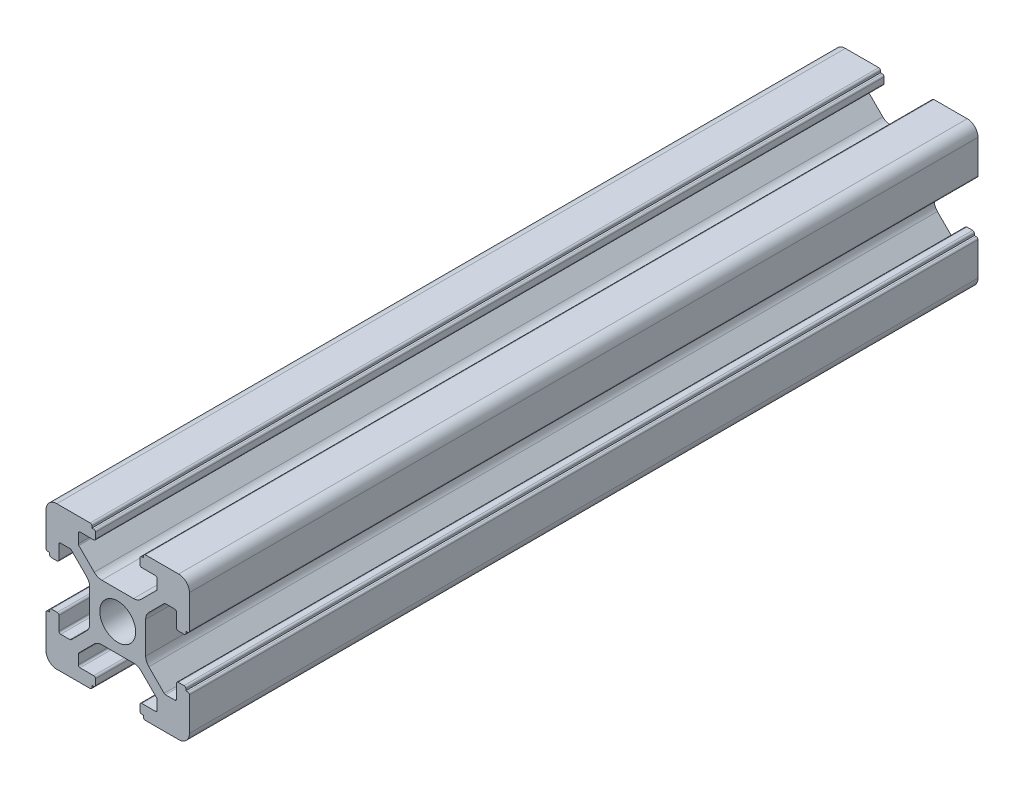
SolidWorks part; units mm, degrees
ref_plane "前视基准面" through (0, 0, 0) normal (0, 0, 1) x (1, 0, 0)
ref_plane "上视基准面" through (0, 0, 0) normal (0, 1, 0) x (1, 0, 0)
ref_plane "右视基准面" through (0, 0, 0) normal (1, 0, 0) x (0, 0, -1)
sketch "草图1" plane through (0, 0, 0) normal (0, 0, 1) x (1, 0, 0)
  line L0 (0, 0) -> (0, 5.5) construction
  line L1 (-8.5023, -10.0023) -> (-3.85, -10.0023)
  line L2 (-10.0023, -8.5023) -> (-10.0023, -3.85)
  line L3 (-8.5023, 10.0023) -> (-3.85, 10.0023)
  line L4 (10.0023, -8.5023) -> (10.0023, -3.85)
  line L5 (-10.0023, -10.0023) -> (10.0023, 10.0023) construction
  line L6 (-10.0023, 10.0023) -> (10.0023, -10.0023) construction
  line L7 (-2.218, -3.9) -> (2.218, -3.9)
  line L8 (-3.9, -2.218) -> (-3.9, 2.218)
  line L9 (-2.218, 3.9) -> (2.218, 3.9)
  line L10 (3.9, -2.218) -> (3.9, 2.218)
  line L11 (-3.9, -3.9) -> (3.9, 3.9) construction
  line L12 (-3.9, 3.9) -> (3.9, -3.9) construction
  line L13 (-5.25, -8.2) -> (-3.35, -8.2)
  line L14 (-8.2, -5.25) -> (-8.2, -3.35)
  line L15 (-5.25, 8.2) -> (-3.35, 8.2)
  line L16 (8.2, -5.25) -> (8.2, -3.35)
  line L17 (-8.2, -8.2) -> (8.2, 8.2) construction
  line L18 (-8.2, 8.2) -> (8.2, -8.2) construction
  line L19 (-7.95, 5.5) -> (-6.6642, 5.5)
  line L20 (0, 0) -> (5.5, 0) construction
  line L23 (-5.5, 7.95) -> (-5.5, 6.6642)
  line L26 (0, 0) -> (-0.5303, 0.5303)
  line L27 (3.2787, 4.3393) -> (5.4268, 6.4874)
  line L28 (0, 0) -> (0.5303, -0.5303)
  line L29 (5.5, 6.6642) -> (5.5, 7.95)
  line L30 (4.3393, 3.2787) -> (6.4874, 5.4268)
  line L31 (6.6642, 5.5) -> (7.95, 5.5)
  line L32 (4.3393, -3.2787) -> (6.4874, -5.4268)
  line L33 (3.2787, -4.3393) -> (5.4268, -6.4874)
  line L34 (-3.2787, -4.3393) -> (-5.4268, -6.4874)
  line L35 (-4.3393, -3.2787) -> (-6.4874, -5.4268)
  line L36 (-4.3393, 3.2787) -> (-6.4874, 5.4268)
  line L37 (-3.2787, 4.3393) -> (-5.4268, 6.4874)
  line L38 (3.1, -8.45) -> (3.1, -9.2523)
  line L39 (8.45, 3.1) -> (9.2523, 3.1)
  line L40 (-5.5, -6.6642) -> (-5.5, -7.95)
  line L41 (-6.6642, -5.5) -> (-7.95, -5.5)
  line L42 (5.5, -6.6642) -> (5.5, -7.95)
  line L43 (6.6642, -5.5) -> (7.95, -5.5)
  line L44 (9.2523, -3.1) -> (8.45, -3.1)
  line L46 (10.0023, 3.85) -> (10.0023, 8.5023)
  line L47 (8.2, 3.35) -> (8.2, 5.25)
  line L48 (-3.1, -9.2523) -> (-3.1, -8.45)
  line L49 (-8.45, -3.1) -> (-9.2523, -3.1)
  line L50 (-9.2523, 3.1) -> (-8.45, 3.1)
  line L51 (-3.1, 8.45) -> (-3.1, 9.2523)
  line L52 (3.1, 9.2523) -> (3.1, 8.45)
  line L53 (3.85, 10.0023) -> (8.5023, 10.0023)
  line L54 (3.35, 8.2) -> (5.25, 8.2)
  line L55 (-10.0023, 3.85) -> (-10.0023, 8.5023)
  line L56 (-8.2, 3.35) -> (-8.2, 5.25)
  line L57 (3.35, -8.2) -> (5.25, -8.2)
  line L58 (3.85, -10.0023) -> (8.5023, -10.0023)
  line L59 (9.7523, -3.6) -> (9.5023, -3.6)
  line L61 (9.7523, 3.6) -> (9.5023, 3.6)
  line L62 (9.5023, -3.6) -> (9.5023, -3.35)
  line L63 (3.6, -9.7523) -> (3.6, -9.5023)
  line L64 (3.35, -9.5023) -> (3.6, -9.5023)
  line L65 (9.5023, 3.35) -> (9.5023, 3.6)
  line L66 (-3.6, -9.5023) -> (-3.35, -9.5023)
  line L67 (-3.6, -9.7523) -> (-3.6, -9.5023)
  line L68 (-9.7523, -3.6) -> (-9.5023, -3.6)
  line L69 (-9.5023, -3.35) -> (-9.5023, -3.6)
  line L70 (-9.5023, 3.6) -> (-9.5023, 3.35)
  line L71 (-9.7523, 3.6) -> (-9.5023, 3.6)
  line L72 (-3.6, 9.7523) -> (-3.6, 9.5023)
  line L73 (-3.35, 9.5023) -> (-3.6, 9.5023)
  line L74 (3.6, 9.5023) -> (3.35, 9.5023)
  line L75 (3.6, 9.7523) -> (3.6, 9.5023)
  circle A0 centre (0, 0) radius 2.5
  arc A1 (10.0023, 8.5023) -> (8.5023, 10.0023) centre (8.5023, 8.5023) ccw
  arc A2 (8.5023, -10.0023) -> (10.0023, -8.5023) centre (8.5023, -8.5023) ccw
  arc A3 (-10.0023, -8.5023) -> (-8.5023, -10.0023) centre (-8.5023, -8.5023) ccw
  arc A4 (-10.0023, 8.5023) -> (-8.5023, 10.0023) centre (-8.5023, 8.5023) cw
  arc A5 (-9.5023, -3.35) -> (-9.2523, -3.1) centre (-9.2523, -3.35) cw
  arc A6 (-9.7523, -3.6) -> (-10.0023, -3.85) centre (-9.7523, -3.85) ccw
  arc A7 (-8.45, -3.1) -> (-8.2, -3.35) centre (-8.45, -3.35) cw
  arc A8 (-7.95, -5.5) -> (-8.2, -5.25) centre (-7.95, -5.25) cw
  arc A9 (-6.4874, -5.4268) -> (-6.6642, -5.5) centre (-6.6642, -5.25) cw
  arc A10 (-5.4268, -6.4874) -> (-5.5, -6.6642) centre (-5.25, -6.6642) ccw
  arc A11 (-5.5, -7.95) -> (-5.25, -8.2) centre (-5.25, -7.95) ccw
  arc A12 (-3.6, -9.7523) -> (-3.85, -10.0023) centre (-3.85, -9.7523) cw
  arc A13 (-3.35, -9.5023) -> (-3.1, -9.2523) centre (-3.35, -9.2523) ccw
  arc A14 (-3.1, -8.45) -> (-3.35, -8.2) centre (-3.35, -8.45) ccw
  arc A15 (3.1, -8.45) -> (3.35, -8.2) centre (3.35, -8.45) cw
  arc A16 (5.5, -7.95) -> (5.25, -8.2) centre (5.25, -7.95) cw
  arc A17 (5.4268, -6.4874) -> (5.5, -6.6642) centre (5.25, -6.6642) cw
  arc A18 (6.4874, -5.4268) -> (6.6642, -5.5) centre (6.6642, -5.25) ccw
  arc A19 (7.95, -5.5) -> (8.2, -5.25) centre (7.95, -5.25) ccw
  arc A20 (8.45, -3.1) -> (8.2, -3.35) centre (8.45, -3.35) ccw
  arc A21 (9.5023, -3.35) -> (9.2523, -3.1) centre (9.2523, -3.35) ccw
  arc A22 (9.7523, -3.6) -> (10.0023, -3.85) centre (9.7523, -3.85) cw
  arc A23 (3.35, -9.5023) -> (3.1, -9.2523) centre (3.35, -9.2523) cw
  arc A24 (3.6, -9.7523) -> (3.85, -10.0023) centre (3.85, -9.7523) ccw
  arc A25 (7.95, 5.5) -> (8.2, 5.25) centre (7.95, 5.25) cw
  arc A26 (8.2, 3.35) -> (8.45, 3.1) centre (8.45, 3.35) ccw
  arc A27 (9.5023, 3.35) -> (9.2523, 3.1) centre (9.2523, 3.35) cw
  arc A28 (9.7523, 3.6) -> (10.0023, 3.85) centre (9.7523, 3.85) ccw
  arc A29 (6.6642, 5.5) -> (6.4874, 5.4268) centre (6.6642, 5.25) ccw
  arc A30 (5.4268, 6.4874) -> (5.5, 6.6642) centre (5.25, 6.6642) ccw
  arc A31 (5.5, 7.95) -> (5.25, 8.2) centre (5.25, 7.95) ccw
  arc A32 (3.1, 8.45) -> (3.35, 8.2) centre (3.35, 8.45) ccw
  arc A33 (3.6, 9.7523) -> (3.85, 10.0023) centre (3.85, 9.7523) cw
  arc A34 (3.35, 9.5023) -> (3.1, 9.2523) centre (3.35, 9.2523) ccw
  arc A35 (-9.7523, 3.6) -> (-10.0023, 3.85) centre (-9.7523, 3.85) cw
  arc A36 (-9.5023, 3.35) -> (-9.2523, 3.1) centre (-9.2523, 3.35) ccw
  arc A37 (-8.45, 3.1) -> (-8.2, 3.35) centre (-8.45, 3.35) ccw
  arc A38 (-8.2, 5.25) -> (-7.95, 5.5) centre (-7.95, 5.25) cw
  arc A39 (-6.4874, 5.4268) -> (-6.6642, 5.5) centre (-6.6642, 5.25) ccw
  arc A40 (-5.4268, 6.4874) -> (-5.5, 6.6642) centre (-5.25, 6.6642) cw
  arc A41 (-5.5, 7.95) -> (-5.25, 8.2) centre (-5.25, 7.95) cw
  arc A42 (-3.1, 8.45) -> (-3.35, 8.2) centre (-3.35, 8.45) cw
  arc A43 (-3.1, 9.2523) -> (-3.35, 9.5023) centre (-3.35, 9.2523) ccw
  arc A44 (-3.6, 9.7523) -> (-3.85, 10.0023) centre (-3.85, 9.7523) ccw
  arc A45 (-4.3393, 3.2787) -> (-3.9, 2.218) centre (-5.4, 2.218) cw
  arc A46 (-3.2787, 4.3393) -> (-2.218, 3.9) centre (-2.218, 5.4) ccw
  arc A47 (3.2787, 4.3393) -> (2.218, 3.9) centre (2.218, 5.4) cw
  arc A48 (4.3393, 3.2787) -> (3.9, 2.218) centre (5.4, 2.218) ccw
  arc A49 (4.3393, -3.2787) -> (3.9, -2.218) centre (5.4, -2.218) cw
  arc A50 (3.2787, -4.3393) -> (2.218, -3.9) centre (2.218, -5.4) ccw
  arc A51 (-4.3393, -3.2787) -> (-3.9, -2.218) centre (-5.4, -2.218) ccw
  arc A52 (-2.218, -3.9) -> (-3.2787, -4.3393) centre (-2.218, -5.4) ccw
  point P0 (0, 0)
  point P7 (10.0023, 0)
  point P62 (0, 0)
  point P76 (0, 0)
  point P92 (-8.2, -5.5)
  point P99 (0, 0)
  point P106 (-5.5, -8.2)
  point P117 (5.5, -8.2)
  point P124 (8.2, -5.5)
  point P137 (8.2, 5.5)
  point P140 (8.2, 3.1)
  point P147 (6.5607, 5.5)
  point P152 (5.5, 8.2)
  point P167 (-8.2, 5.5)
  point P174 (-5.5, 8.2)
  dimension "D1" = 1.5
  dimension "D5" = 0.25
  dimension "D6" = 1.5
  dimension "D2" = 4
  dimension "D3" = 4
  dimension "D4" = 4
extrude "凸台-拉伸1" add sketch "草图1" along normal blind 110 contours A52 L7 A50 L33 A17 L42 A16 L57 A15 L38 A23 L64 L63 A24 L58 A2 L4 A22 L59 L62 A21 L44 A20 L16 A19 L43 A18 L32 A49 L10 A48 L30 A29 L31 A25 L47 A26 L39 A27 L65 L61 A28 L46 A1 L53 A33 L75 L74 A34 L52 A32
